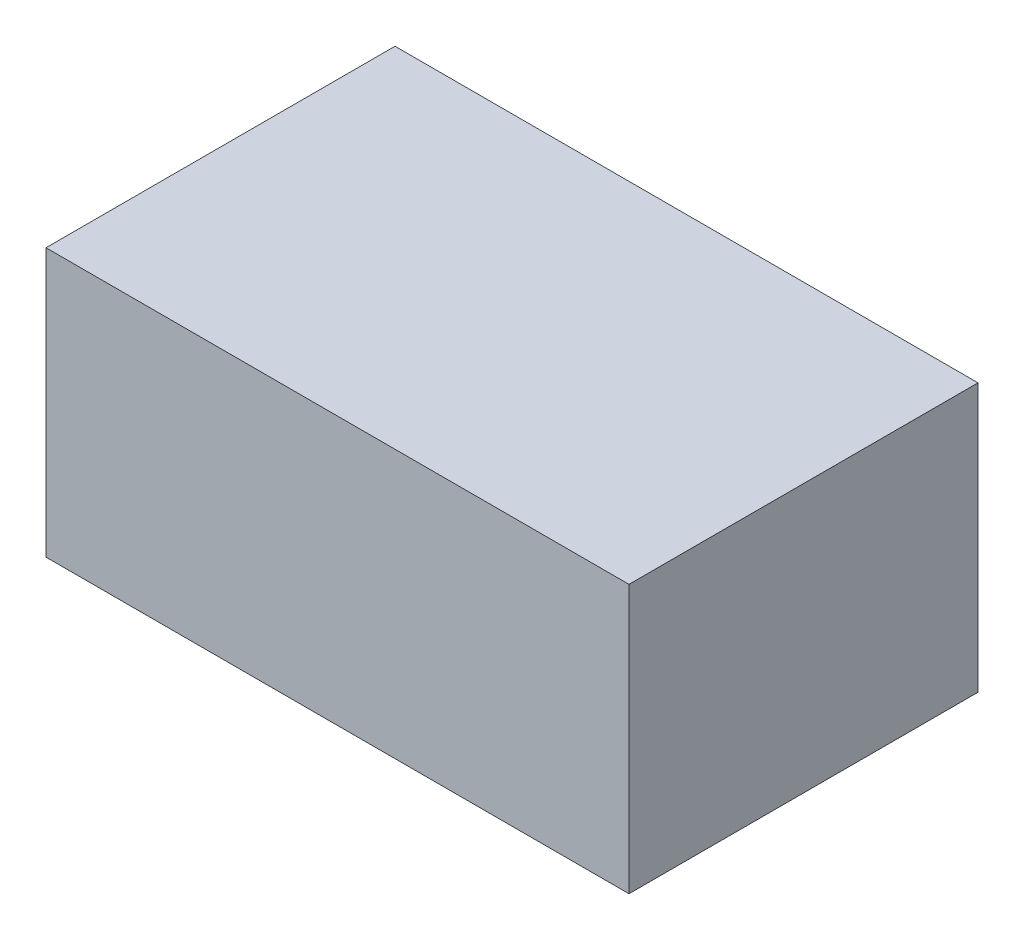
SolidWorks part; units mm, degrees
ref_plane "Front Plane" through (0, 0, 0) normal (0, 0, 1) x (1, 0, 0)
ref_plane "Top Plane" through (0, 0, 0) normal (0, 1, 0) x (1, 0, 0)
ref_plane "Right Plane" through (0, 0, 0) normal (1, 0, 0) x (0, 0, -1)
sketch "Sketch1" plane through (0, 0, 0) normal (0, 0, 1) x (1, 0, 0)
  line L1 (-22.3, -10.25) -> (22.3, -10.25)
  line L2 (-22.3, -10.25) -> (-22.3, 10.25)
  line L3 (-22.3, 10.25) -> (22.3, 10.25)
  line L4 (22.3, -10.25) -> (22.3, 10.25)
  line L5 (-22.3, -10.25) -> (22.3, 10.25) construction
  line L6 (-22.3, 10.25) -> (22.3, -10.25) construction
  point P0 (0, 0)
extrude "Envelope" add sketch "Sketch1" along normal blind 26.7
